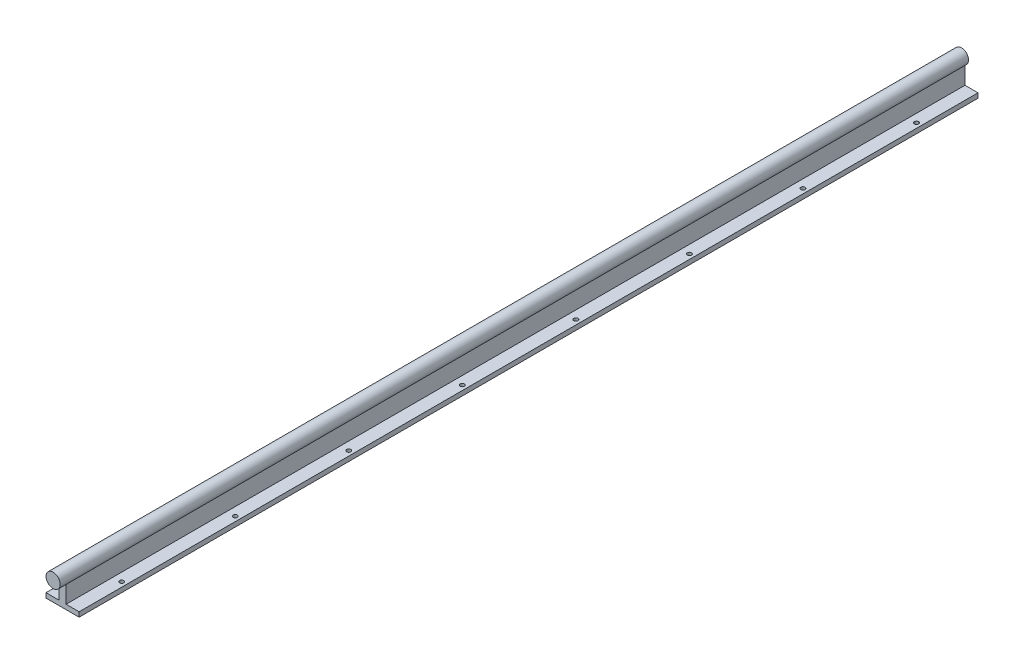
SolidWorks part; units mm, degrees
ref_plane "Front" through (0, 0, 0) normal (0, 0, 1) x (1, 0, 0)
ref_plane "Top" through (0, 0, 0) normal (0, 1, 0) x (1, 0, 0)
ref_plane "Right" through (0, 0, 0) normal (1, 0, 0) x (0, 0, -1)
sketch "Sketch1" plane through (0, 0, 0) normal (0, 0, 1) x (1, 0, 0)
  line L0 (-22.225, -38.1) -> (22.225, -38.1)
  line L1 (22.225, -38.1) -> (22.225, -31.75)
  line L2 (22.225, -31.75) -> (4.7625, -31.75)
  line L3 (4.7625, -31.75) -> (4.7625, -8.2489)
  line L4 (-22.225, -38.1) -> (-22.225, -31.75)
  line L5 (-22.225, -31.75) -> (-4.7625, -31.75)
  line L6 (-4.7625, -31.75) -> (-4.7625, -8.2489)
  arc A0 (4.7625, -8.2489) -> (-4.7625, -8.2489) centre (0, 0) ccw
  dimension "D1" = 19.05
  dimension "D2" = 38.1
  dimension "D3" = 44.45
  dimension "D4" = 9.525
  dimension "D5" = 6.35
extrude "Extrude1" add sketch "Sketch1" along normal blind 1219.2
hole_wizard "#10 Clearance Hole1" positions "Sketch3" profile "Sketch2" hole size "#10" standard "Ansi Inch" end condition up to next
sketch "Sketch3" plane through (0, -38.1, 0) normal (0, -1, 0) x (1, 0, 0)
  line L0 (-22.225, 0) -> (22.225, 0) construction
  point P1 (-15.875, 76.2)
  point P3 (15.875, 76.2)
  dimension "D1" = 15.875
  dimension "D2" = 31.75
  dimension "D3" = 76.2
sketch "Sketch2" plane through (-15.875, -38.1, 76.2) normal (1, 0, 0) x (0, 0, -1)
  line L0 (0, 0) -> (0, 6.35)
  line L1 (0, 6.35) -> (2.8067, 6.35)
  line L2 (2.8067, 6.35) -> (2.8067, 0)
  line L5 (2.8067, 0) -> (0, 0)
  line L11 (0, -6.35) -> (0, 107.95) construction
  dimension "Thru Hole Dia." = 5.6134
  dimension "Thru Hole Depth" = 6.35
pattern_linear "LPattern3" count 8 spacing 152.4 along (0, 0, 1) of "#10 Clearance Hole1"
sketch "Sketch4" plane through (0, 0, 1219.2) normal (0, 0, 1) x (1, 0, 0)
  circle A0 centre (0, 0) radius 9.525
  arc A1 (4.7625, -8.2489) -> (-4.7625, -8.2489) centre (0, 0) ccw construction
extrude "Cut-Extrude1" cut sketch "Sketch4" against normal blind 12.7 flip side to cut
